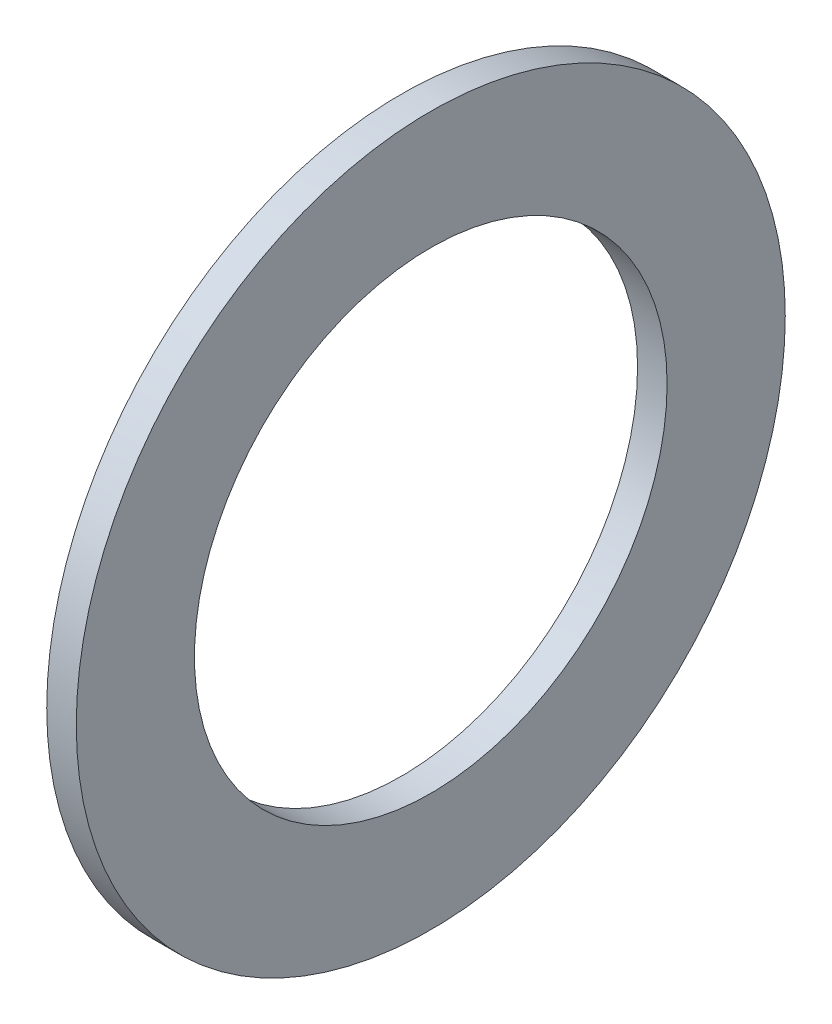
SolidWorks part; units mm, degrees
material "E-Glass Fiber"
ref_plane "Front Plane" through (0, 0, 0) normal (0, 0, 1) x (1, 0, 0)
ref_plane "Top Plane" through (0, 0, 0) normal (0, 1, 0) x (1, 0, 0)
ref_plane "Right Plane" through (0, 0, 0) normal (1, 0, 0) x (0, 0, -1)
sketch "Sketch1" plane through (0, 0, 0) normal (1, 0, 0) x (0, 0, -1)
  circle A0 centre (0, 0) radius 76.2
  circle A1 centre (0, 0) radius 50.8
  dimension "D1" = 152.4
  dimension "D2" = 101.6
extrude "Boss-Extrude1" add sketch "Sketch1" along normal blind 6.35
